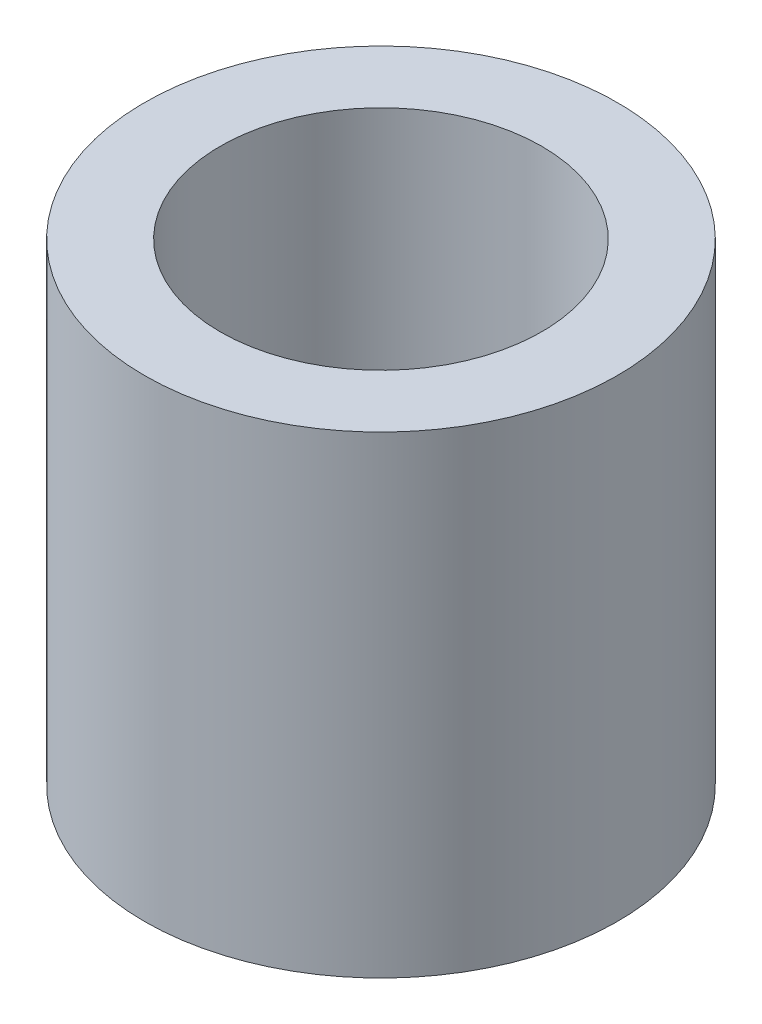
SolidWorks part; units mm, degrees
ref_plane "Front Plane" through (0, 0, 0) normal (0, 0, 1) x (1, 0, 0)
ref_plane "Top Plane" through (0, 0, 0) normal (0, 1, 0) x (1, 0, 0)
ref_plane "Right Plane" through (0, 0, 0) normal (1, 0, 0) x (0, 0, -1)
sketch "Sketch1" plane through (0, 0, 0) normal (0, 1, 0) x (1, 0, 0)
  circle A0 centre (0, 0) radius 1.7
  circle A1 centre (0, 0) radius 2.5
  dimension "D1" = 3.4
  dimension "D2" = 5
extrude "Boss-Extrude1" add sketch "Sketch1" along normal blind 5
